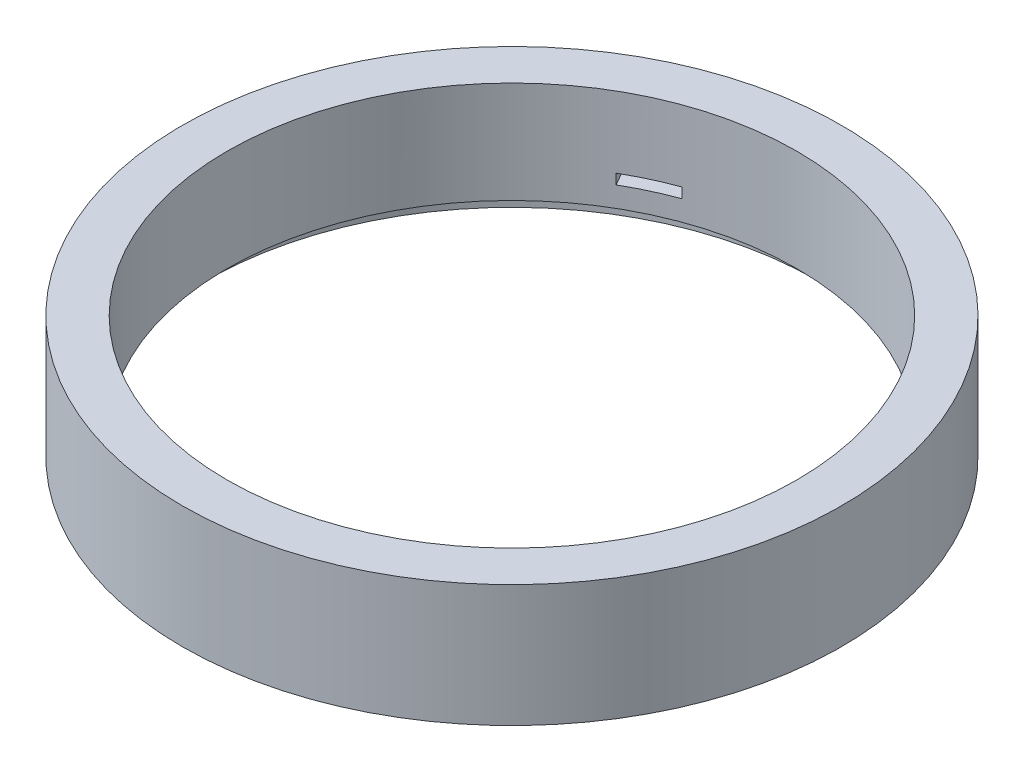
SolidWorks part; units mm, degrees
material "ABS"
ref_plane "前基準面" through (0, 0, 0) normal (0, 0, 1) x (1, 0, 0)
ref_plane "上基準面" through (0, 0, 0) normal (0, 1, 0) x (1, 0, 0)
ref_plane "右基準面" through (0, 0, 0) normal (1, 0, 0) x (0, 0, -1)
sketch "草圖1" plane through (0, 0, 0) normal (0, 1, 0) x (1, 0, 0)
  circle A0 centre (0, 0) radius 81
  circle A1 centre (0, 0) radius 70
  dimension "D1" = 162
  dimension "D2" = 140
extrude "填料-伸長1" add sketch "草圖1" along normal mid plane 30
sketch "草圖2" plane through (0, 0, 0) normal (0, 0, 1) x (1, 0, 0)
  line L0 (-81, -15) -> (81, -15) construction
  line L1 (69.9984, -5) -> (74.9984, -5)
  line L2 (69.9984, -5) -> (69.9984, -2.5)
  line L3 (69.9984, -2.5) -> (74.9984, -2.5)
  line L4 (74.9984, -5) -> (74.9984, -2.5)
  dimension "D1" = 5
  dimension "D2" = 2.5
  dimension "D3" = 10
revolve "除料-旋轉1" cut sketch "草圖2" angle 10 about axis through (0, 15, 0) along (0, -1, 0)
pattern_circular "環狀複製排列1" count 3 over 360 about axis through (0, 0, 0) along (0, 1, 0) of "除料-旋轉1"
sketch "草圖3" plane through (0, -15, 0) normal (0, -1, 0) x (1, 0, 0)
  circle A0 centre (0, 0) radius 75
  dimension "D1" = 150
extrude "除料-伸長1" cut sketch "草圖3" against normal blind 5
equation "\"M\"= 1'模数"
equation "\"Z1\"= 136'齿数"
equation "\"Z2\"= 17'配对齿数(小齿轮)"
equation "\"B\"= 5'齿宽"
equation "\"Dmax\"= 150'最外圆"
equation "\"Z2_\"= IIF ( \"Z2\" < \"Z1\" , int ( \"Z2\" ) , int ( \"Z1\" / 2 ) )'配对齿数默认值"
equation "\"Alpha\"= 20                            '压力角"
equation "\"D\"= \"M\" * \"Z1\"                      '分度圆"
equation "\"Db\"= \"D\" * cos ( \"Alpha\" )     '基圆"
equation "\"Hax\"= 1                                 '齿顶高系数"
equation "\"Cx\"= 0.25                              '顶隙系数"
equation "\"Ha\"= \"Hax\" * \"M\"                  '齿顶高"
equation "\"Hf\"= ( \"Hax\" + \"Cx\" ) * \"M\"   '齿根高"
equation "\"Df\"= \"D\" + 2 * \"Hf\"                '齿根圆"
equation "\"Da\"= \"D\" - 2 * \"Ha\"+\"Delta_Da\"               '齿顶圆"
equation "\"Delta_Da\"= 2 * \"Hax\" ^ 2 * \"M\" / ( \"Z2_\" * ( tan ( \"Alpha\" ) ) ^ 2 )"
equation "\"草圖7\"= IIF ( \"Db\" < \"Da\" , \"unsuppressed\" , \"suppressed\" )"
equation "\"除料-伸長2\" = IIF ( \"Db\" < \"Da\" , \"unsuppressed\" , \"suppressed\" )"
equation "\"環狀複製排列4\"= IIF ( \"Db\" < \"Da\" , \"unsuppressed\" , \"suppressed\" )"
